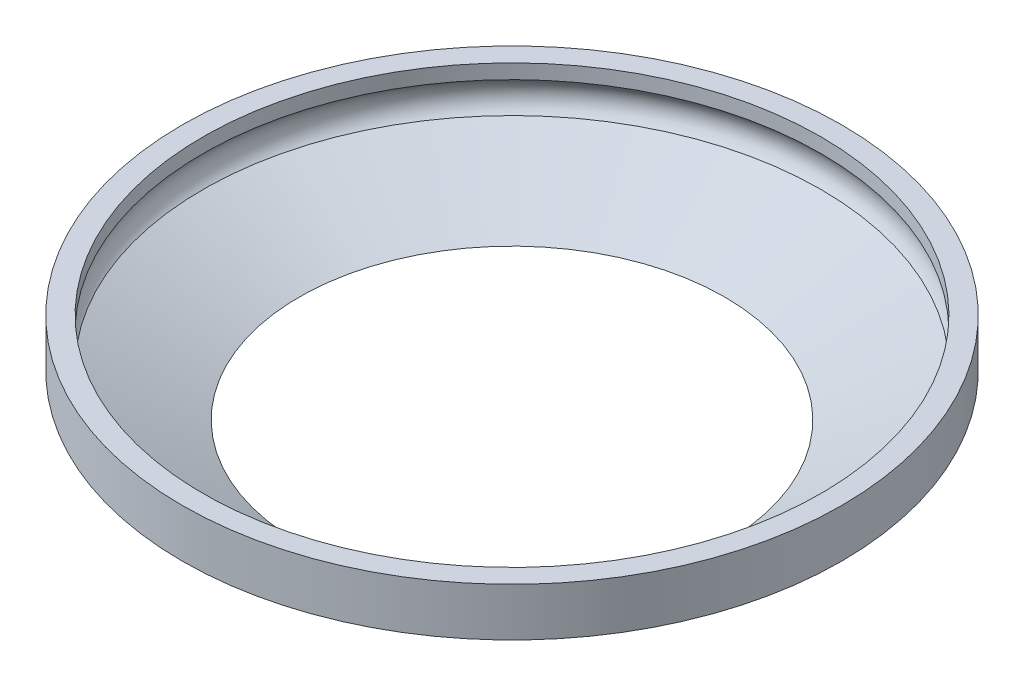
SolidWorks part; units mm, degrees
ref_plane "Front Plane" through (0, 0, 0) normal (0, 0, 1) x (1, 0, 0)
ref_plane "Top Plane" through (0, 0, 0) normal (0, 1, 0) x (1, 0, 0)
ref_plane "Right Plane" through (0, 0, 0) normal (1, 0, 0) x (0, 0, -1)
sketch "Sketch1" plane through (0, 0, 0) normal (0, 0, 1) x (1, 0, 0)
  line L0 (0, 0) -> (0, 42) construction
  line L1 (0, 0) -> (-29, 0) construction
  line L2 (-29, 0) -> (-29, 42) construction
  line L3 (-29, 42) -> (0, 42) construction
  line L4 (-29, 0) -> (-29, 0.8) construction
  line L6 (-11, 20) -> (-11, 42) construction
  line L7 (-11, 42) -> (-10.2, 42) construction
  line L11 (-29, 0) -> (-23.5755, 0) construction
  line L12 (-29, 0.8) -> (-24, 0.8) construction
  line L13 (-24, 0.8) -> (-11, 20) construction
  line L14 (-10.2, 19.7546) -> (-23.5755, 0) construction
  line L15 (0, 0) -> (0, -1) construction
  line L16 (0, -1) -> (-29, -1) construction
  line L17 (-10.2, 19.7546) -> (-10.2, 42) construction
  line L18 (-29, -1) -> (-29, 0) construction
  line L19 (-29, -5.6) -> (-23.5755, -2) construction
  line L20 (-10.2, -21.7546) -> (-23.5755, -2) construction
  line L21 (-10.2, -21.7546) -> (-10.2, -44) construction
  line L22 (-11, -44) -> (-10.2, -44) construction
  line L23 (-11, -22) -> (-11, -44) construction
  line L24 (-24, -2.8) -> (-11, -22) construction
  line L25 (-29, -2.8) -> (-24, -2.8) construction
  line L26 (-29, -5.6) -> (-29, -2.8) construction
  line L27 (-28, 0.8) -> (-28, 1.8) construction
  line L28 (-28, 1.8) -> (-21.2917, 4.8) construction
  line L29 (-21.2917, 4.8) -> (-24, 0.8) construction
  line L30 (-24, 0.8) -> (-28, 0.8) construction
  line L31 (-21.2917, -6.8) -> (-24, -2.8) construction
  line L32 (-28, -3.8) -> (-21.2917, -6.8) construction
  line L33 (-28, -2.8) -> (-28, -3.8) construction
  line L34 (-24, -2.8) -> (-28, -2.8) construction
  line L35 (-21.2917, 4.8) -> (-28, 1.8)
  line L36 (-28, 1.8) -> (-28, 0.8)
  line L37 (-28, 0.8) -> (-29, 0.8)
  line L38 (-29, 0.8) -> (-29, -5.6)
  line L39 (-29, -5.6) -> (-29.8, -5.6)
  line L42 (-19.5895, 7.3139) -> (-21.2917, 4.8)
  line L43 (-19.5895, 7.3139) -> (-29.9743, 2.6698)
  line L44 (-29.9743, 2.6698) -> (-31.8, 1.8533)
  line L45 (-31.8, 1.8533) -> (-31.8, 1.4)
  line L46 (-31.8, 1.4) -> (-29.8, 1.4)
  line L47 (-29.8, 1.4) -> (-29.8, -0.6)
  line L48 (-29.8, -3.6) -> (-29.8, -5.6)
  arc A0 (-29.8, -3.6) -> (-29.8, -0.6) centre (-28.5429, -2.1) cw
  point P37 (-30.5, -2.1)
  dimension "D10" = 0.8
  dimension "D11" = 1
  dimension "D14" = 55.899
  dimension "D13" = 0.8
  dimension "D2" = 29
  dimension "D3" = 0.8
  dimension "D4" = 42
  dimension "D5" = 22
  dimension "D6" = 11
  dimension "D7" = 1
  dimension "D8" = 1
  dimension "D9" = 5
  dimension "D12" = 4
  dimension "D15" = 3
  dimension "D16" = 1.6
  dimension "D17" = 2
  dimension "D18" = 0.7
  dimension ".7" = 2
  dimension "D19" = 2
  dimension "D20" = 2
  dimension "D21" = 6.4
sketch "Sketch2" plane through (0, 0, 0) normal (0, 0, 1) x (1, 0, 0)
  line L0 (-28, 1.8) -> (-21.2917, 4.8) construction
  line L1 (-28, 0.8) -> (-28, 1.8) construction
  line L2 (-29, 0.8) -> (-24, 0.8) construction
  line L3 (-10.2, 19.7546) -> (-23.5755, 0) construction
  line L4 (-24, 0.8) -> (-11, 20) construction
  line L5 (-10.2, 19.7546) -> (-10.2, 42) construction
  line L6 (-11, 20) -> (-11, 42) construction
  line L7 (-28, 1.8) -> (-21.2917, 4.8)
  line L8 (-28, 0.8) -> (-28, 1.8)
  line L9 (-29, 0.8) -> (-28, 0.8)
  line L10 (-10.2, 19.7546) -> (-23.5755, 0)
  line L11 (-21.2917, 4.8) -> (-11, 20)
  line L12 (-10.2, 19.7546) -> (-10.2, 42)
  line L13 (-11, 20) -> (-11, 42)
  line L14 (-29, 0.8) -> (-29, 0)
  line L15 (-29, 0) -> (-23.5755, 0)
  line L16 (-11, 42) -> (-10.2, 42)
sketch "Sketch3" plane through (0, 0, 0) normal (0, 0, 1) x (1, 0, 0)
  line L0 (-28, -2.8) -> (-28, -3.8)
  line L1 (-28, -3.8) -> (-21.2917, -6.8)
  line L2 (-21.2917, -6.8) -> (-19.5895, -9.3139)
  line L3 (-24, -2.8) -> (-11, -22) construction
  line L4 (-19.5895, -9.3139) -> (-31.8, -3.8533)
  line L5 (-31.8, -3.8533) -> (-31.8, 1.4)
  line L6 (-31.8, 1.4) -> (-29.8, 1.4)
  line L7 (-29.8, 1.4) -> (-29.8, -0.6)
  line L8 (-31.8, 1.8533) -> (-31.8, 1.4) construction
  line L9 (-19.5895, 7.3139) -> (-21.2917, 4.8) construction
  line L10 (-29.8, -3.6) -> (-29.8, -2.8)
  line L11 (-29.8, -2.8) -> (-28, -2.8)
  arc A0 (-29.8, -0.6) -> (-29.8, -3.6) centre (-28.5429, -2.1) ccw construction
  arc A1 (-29.8, -0.6) -> (-29.8, -3.6) centre (-28.5429, -2.1) ccw
revolve "Revolve2" add sketch "Sketch3" angle 360 about L0
ref_plane "Plane1" through (0, -9.3139, 0) normal (0, 1, 0) x (1, 0, 0)
sketch "Sketch4" plane through (0, -9.3139, 0) normal (0, 1, 0) x (1, 0, 0)
  circle A0 centre (0, 0) radius 21
  dimension "D1" = 42
extrude "Cut-Extrude1" cut sketch "Sketch4" along normal blind 1.37 draft 50 draft outward yes
sketch "Sketch5" plane through (0, 0, 0) normal (0, 0, 1) x (1, 0, 0)
  line L0 (-29.8, 1.4) -> (-29.8, -0.6)
  line L1 (-31.8, 1.4) -> (-29.8, 1.4)
  line L2 (-31.8, 1.4) -> (-31.8, 0.8)
  line L3 (-31.8, 0.8) -> (-29.8, 0.8)
  line L4 (-29.8, 1.4) -> (-29.8, 0.8)
  line L5 (29.8, -0.6) -> (29.8, 1.4)
  line L6 (29.8, -0.6) -> (29.8, 1.4)
  line L7 (-29.8, 1.4) -> (-29.8, -0.6) construction
  line L8 (0, 0) -> (0, 13.0077) construction
  dimension "D1" = 0.6
revolve "Cut-Revolve1" cut sketch "Sketch5" angle 360 about L8
sketch "Sketch6" plane through (0, 0, 0) normal (0, 0, 1) x (1, 0, 0)
  line L0 (-29.8, -2.8) -> (-28, -2.8)
  line L1 (-28, -2.8) -> (-28, -3.8)
  line L2 (-28, -3.8) -> (-29.8, -2.8)
  line L3 (21.2917, -6.8) -> (28, -3.8)
  line L4 (-28, -3.8) -> (-21.2917, -6.8)
  line L5 (-28, -3.8) -> (-21.2917, -6.8)
  line L6 (21.2917, -6.8) -> (28, -3.8) construction
  line L7 (-28, -2.8) -> (-28, -3.8)
  line L8 (28, -3.8) -> (28, -2.8)
  line L9 (28, -3.8) -> (28, -2.8) construction
  line L10 (-28, -2.8) -> (-28, -3.8)
  line L11 (-29.8, -2.8) -> (-28, -2.8)
  line L12 (28, -2.8) -> (29.8, -2.8)
  line L13 (28, -2.8) -> (29.8, -2.8) construction
  line L14 (-29.8, -2.8) -> (-28, -2.8)
  line L15 (0, 0) -> (0, 11.7356) construction
revolve "Cut-Revolve2" cut sketch "Sketch6" angle 360 about L15
sketch "Sketch7" plane through (0, 0, 0) normal (0, 0, 1) x (1, 0, 0)
  line L0 (21.2917, -6.8) -> (28, -3.8)
  line L1 (-28, -3.8) -> (-21.2917, -6.8)
  line L2 (-28, -3.8) -> (-21.2917, -6.8)
  line L3 (21.2917, -6.8) -> (28, -3.8) construction
  line L4 (20.5171, -7.9439) -> (21.2917, -6.8)
  line L5 (-21.2917, -6.8) -> (-20.5171, -7.9439)
  line L6 (-21.2917, -6.8) -> (-20.5171, -7.9439)
  line L7 (20.5171, -7.9439) -> (21.2917, -6.8) construction
  line L8 (28, -3.8) -> (29.8, -2.8)
  line L9 (-29.8, -2.8) -> (-28, -3.8)
  line L10 (-29.8, -2.8) -> (-28, -3.8)
  line L11 (28, -3.8) -> (29.8, -2.8) construction
  line L12 (-29.8, -3.6) -> (-29.8, -2.8)
  line L13 (29.8, -2.8) -> (29.8, -3.6)
  line L14 (29.8, -2.8) -> (29.8, -3.6) construction
  line L15 (-29.8, -3.6) -> (-29.8, -2.8)
  line L16 (-29.8, -3.6) -> (-20.5171, -7.9439)
  line L17 (0, 0) -> (0, 7.6448) construction
revolve "Cut-Revolve3" cut sketch "Sketch7" angle 360 about L17
